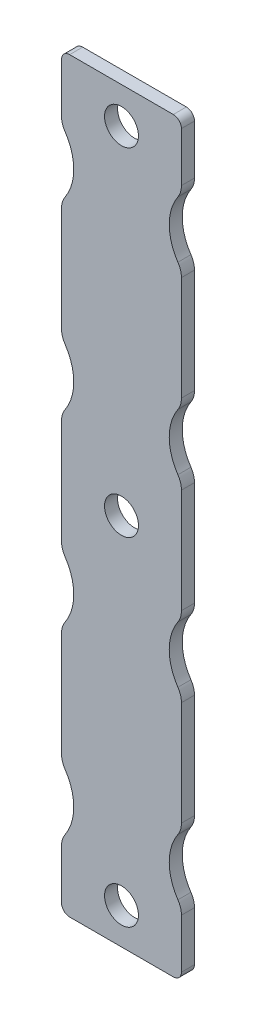
SolidWorks part; units mm, degrees
material "3003 Alloy"
ref_plane "X-Y Datum" through (0, 0, 0) normal (0, 0, 1) x (1, 0, 0)
ref_plane "X-Z Datum" through (0, 0, 0) normal (0, 1, 0) x (1, 0, 0)
ref_plane "Y-Z Datum" through (0, 0, 0) normal (1, 0, 0) x (0, 0, -1)
sketch "Sketch1" plane through (0, 0, 0) normal (0, 0, 1) x (1, 0, 0)
  line L0 (13.703, 64.5059) -> (16.8331, 64.5059) construction
  line L1 (7.903, 75.0059) -> (22.633, 75.0059)
  line L2 (7.903, 75.0059) -> (7.903, 68.5494)
  line L3 (7.903, -13.8121) -> (22.633, -13.8121)
  line L9 (22.633, 75.0059) -> (22.633, 68.5494)
  line L11 (15.268, 64.5059) -> (15.268, 75.0059) construction
  line L13 (7.903, 30.5969) -> (22.633, 30.5969) construction
  line L19 (7.903, 60.4624) -> (7.903, 45.9434)
  line L20 (7.903, 37.8564) -> (7.903, 23.3374)
  line L21 (7.903, 15.2504) -> (7.903, 0.7314)
  line L22 (7.903, -7.3556) -> (7.903, -13.8121)
  line L23 (22.633, -7.3556) -> (22.633, -13.8121)
  line L24 (22.633, 15.2504) -> (22.633, 0.7314)
  line L25 (22.633, 37.8564) -> (22.633, 23.3374)
  line L26 (22.633, 60.4624) -> (22.633, 45.9434)
  circle A4 centre (3.203, -3.3121) radius 4.7 construction
  arc A5 (7.903, -7.3556) -> (7.903, 0.7314) centre (3.203, -3.3121) ccw
  circle A14 centre (15.268, 72.0431) radius 2.5146 construction
  circle A15 centre (15.268, 72.0431) radius 2.0828
  circle A16 centre (15.268, -10.8494) radius 2.0828
  circle A17 centre (15.268, -10.8494) radius 2.5146 construction
  arc A18 (7.903, 15.2504) -> (7.903, 23.3374) centre (3.203, 19.2939) ccw
  arc A19 (7.903, 37.8564) -> (7.903, 45.9434) centre (3.203, 41.8999) ccw
  arc A20 (7.903, 60.4624) -> (7.903, 68.5494) centre (3.203, 64.5059) ccw
  arc A21 (22.633, -7.3556) -> (22.633, 0.7314) centre (27.333, -3.3121) cw
  arc A22 (22.633, 15.2504) -> (22.633, 23.3374) centre (27.333, 19.2939) cw
  arc A23 (22.633, 37.8564) -> (22.633, 45.9434) centre (27.333, 41.8999) cw
  arc A24 (22.633, 60.4624) -> (22.633, 68.5494) centre (27.333, 64.5059) cw
  dimension "D1" = 4
extrude "Boss-Extrude1" add sketch "Sketch1" along normal blind 1.6
fillet "Fillet1" radius 2.54 16 edges at (7.903, 68.5494, 0.8) (7.903, 60.4624, 0.8) (7.903, 45.9434, 0.8) (7.903, 37.8564, 0.8) (7.903, 23.3374, 0.8) (7.903, 15.2504, 0.8) (7.903, 0.7314, 0.8) (7.903, -7.3556, 0.8) (22.633, -7.3556, 0.8) (22.633, 0.7314, 0.8) (22.633, 15.2504, 0.8) (22.633, 23.3374, 0.8) (22.633, 45.9434, 0.8) (22.633, 37.8564, 0.8) (22.633, 68.5494, 0.8) (22.633, 60.4624, 0.8)
sketch "Sketch2" plane through (0, 0, 1.6) normal (0, 0, 1) x (1, 0, 0)
  line L1 (7.903, 75.0059) -> (22.633, 75.0059)
  line L2 (7.903, 75.0059) -> (7.903, -13.8121)
  line L3 (7.903, -13.8121) -> (22.633, -13.8121)
  line L4 (22.633, 75.0059) -> (22.633, -13.8121)
sketch "Sketch3" plane through (0, 0, 1.6) normal (0, 0, 1) x (1, 0, 0)
  line L0 (15.268, 75.0059) -> (15.268, -13.8121) construction
  line L1 (22.633, 75.0059) -> (7.903, 75.0059) construction
  line L2 (7.903, -13.8121) -> (22.633, -13.8121) construction
  circle A0 centre (15.268, 30.5969) radius 2.0828
extrude "Cut-Extrude1" cut sketch "Sketch3" against normal through all
sketch "Sketch4" plane through (0, 0, 1.6) normal (0, 0, 1) x (1, 0, 0)
  line L0 (15.268, -15.015) -> (15.268, -15.269) construction
  line L1 (7.903, 30.5969) -> (37.9882, 30.5969) construction
  line L2 (7.903, -13.8121) -> (22.633, -13.8121)
  line L3 (7.903, -13.8121) -> (7.903, -15.269)
  line L4 (7.903, -15.269) -> (22.633, -15.269)
  line L5 (22.633, -13.8121) -> (22.633, -15.269)
  line L7 (7.903, 76.4627) -> (22.633, 76.4627)
  line L8 (22.633, 75.0059) -> (22.633, 76.4627)
  line L9 (7.903, 75.0059) -> (22.633, 75.0059)
  line L10 (7.903, 75.0059) -> (7.903, 76.4627)
  circle A1 centre (15.268, -10.8494) radius 4.1656 construction
extrude "Boss-Extrude2" add sketch "Sketch4" against normal through all
fillet "Fillet2" radius 1 4 edges at (7.903, -15.269, 0.8) (22.633, -15.269, 0.8) (22.633, 76.4627, 0.8) (7.903, 76.4627, 0.8)
sketch "Sketch5" plane through (0, 0, 1.6) normal (0, 0, 1) x (1, 0, 0)
  line L0 (15.268, 72.0431) -> (15.268, 72.7931)
  circle A0 centre (15.268, 76.9581) radius 4.165
